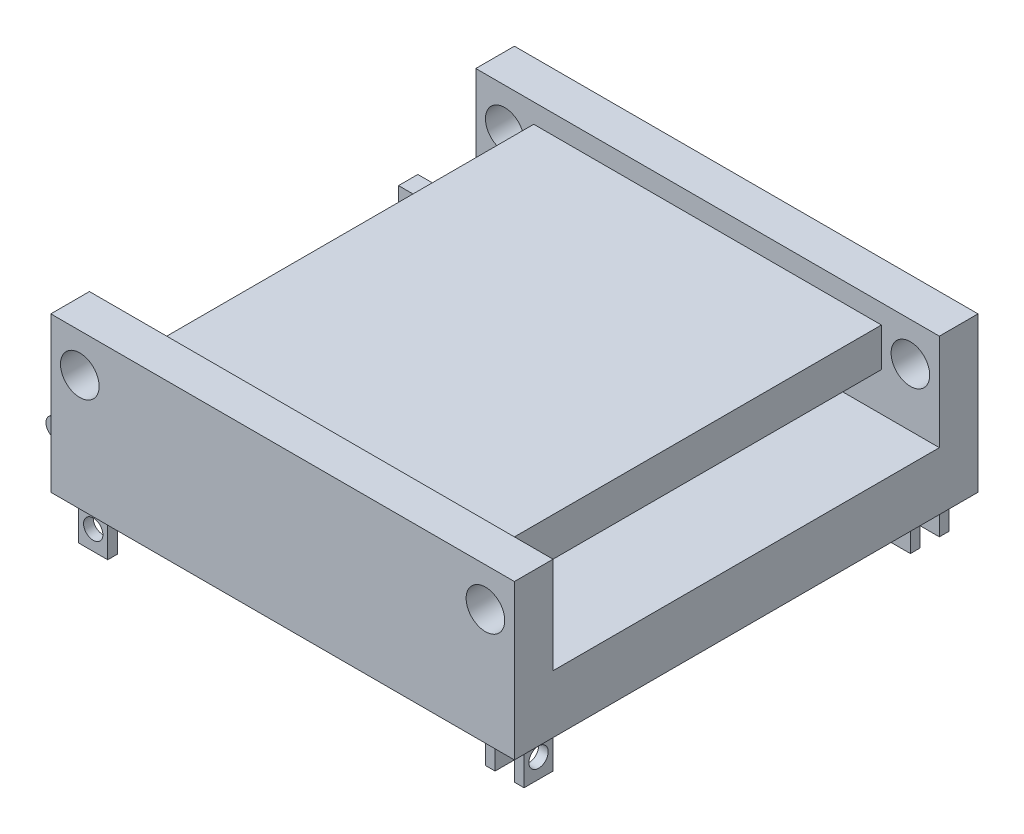
SolidWorks part; units mm, degrees
ref_plane "Front Plane" through (0, 0, 0) normal (0, 0, 1) x (1, 0, 0)
ref_plane "Top Plane" through (0, 0, 0) normal (0, 1, 0) x (1, 0, 0)
ref_plane "Right Plane" through (0, 0, 0) normal (1, 0, 0) x (0, 0, -1)
sketch "Sketch1" plane through (0, 0, 0) normal (0, 1, 0) x (1, 0, 0)
  line L0 (0, 0) -> (1219.2, 0)
  line L1 (1219.2, 0) -> (1219.2, 101.6)
  line L2 (1219.2, 101.6) -> (1117.6, 101.6)
  line L3 (1117.6, 101.6) -> (1117.6, 1117.6)
  line L4 (1117.6, 1117.6) -> (1219.2, 1117.6)
  line L5 (1219.2, 1117.6) -> (1219.2, 1219.2)
  line L6 (1219.2, 1219.2) -> (0, 1219.2)
  line L7 (0, 1219.2) -> (0, 1117.6)
  line L8 (0, 1117.6) -> (101.6, 1117.6)
  line L9 (101.6, 1117.6) -> (101.6, 101.6)
  line L10 (101.6, 101.6) -> (0, 101.6)
  line L11 (0, 101.6) -> (0, 0)
extrude "Boss-Extrude1" add sketch "Sketch1" along normal blind 203.2
sketch "Sketch2" plane through (0, 203.2, 0) normal (0, 1, 0) x (1, 0, 0)
  line L0 (101.6, 1117.6) -> (1117.6, 1117.6)
  line L1 (1117.6, 1117.6) -> (1117.6, 101.6)
  line L2 (1219.2, 101.6) -> (1117.6, 101.6) construction
  line L3 (1117.6, 101.6) -> (1117.6, 1117.6) construction
  line L4 (1117.6, 101.6) -> (101.6, 101.6)
  line L5 (101.6, 101.6) -> (101.6, 1117.6)
extrude "Cut-Extrude1" cut sketch "Sketch2" against normal blind 50.8
sketch "Sketch3" plane through (0, 0, 0) normal (0, -1, 0) x (-1, 0, 0)
  line L0 (-101.6, 101.6) -> (-1117.6, 101.6)
  line L1 (-1117.6, 101.6) -> (-1117.6, 1117.6)
  line L2 (-1117.6, 1117.6) -> (-101.6, 1117.6)
  line L3 (-101.6, 1117.6) -> (-101.6, 101.6)
extrude "Cut-Extrude2" cut sketch "Sketch3" against normal blind 50.8
sketch "Sketch4" plane through (1117.6, 0, 0) normal (1, 0, 0) x (0, 0, -1)
  line L0 (101.6, 152.4) -> (1117.6, 152.4)
  line L1 (1117.6, 152.4) -> (1117.6, 50.8)
  line L2 (1117.6, 50.8) -> (101.6, 50.8)
  line L3 (101.6, 50.8) -> (101.6, 152.4)
extrude "Cut-Extrude3" cut sketch "Sketch4" against normal blind 50.8
sketch "Sketch5" plane through (101.6, 0, 0) normal (-1, 0, 0) x (0, 0, 1)
  line L0 (-1117.6, 152.4) -> (-101.6, 152.4)
  line L1 (-101.6, 152.4) -> (-101.6, 50.8)
  line L2 (-101.6, 50.8) -> (-1117.6, 50.8)
  line L3 (-1117.6, 50.8) -> (-1117.6, 152.4)
extrude "Cut-Extrude4" cut sketch "Sketch5" against normal blind 50.8
sketch "Sketch6" plane through (0, 0, 0) normal (0, 0, 1) x (1, 0, 0)
  line L0 (1219.2, 101.6) -> (1143, 101.6)
  line L1 (1219.2, 203.2) -> (1219.2, 0) construction
  circle A0 centre (1143, 101.6) radius 50.8
extrude "Cut-Extrude5" cut sketch "Sketch6" against normal blind 1270
sketch "Sketch7" plane through (0, 0, -1219.2) normal (0, 0, -1) x (-1, 0, 0)
  line L0 (0, 101.6) -> (-76.2, 101.6)
  line L1 (0, 203.2) -> (0, 0) construction
  circle A0 centre (-76.2, 101.6) radius 50.8
extrude "Cut-Extrude6" cut sketch "Sketch7" against normal blind 1270
sketch "Sketch8" plane through (0, 0, 0) normal (0, -1, 0) x (-1, 0, 0)
  line L0 (0, 0) -> (-1219.2, 0)
  line L1 (-1219.2, 0) -> (-1219.2, 101.6)
  line L2 (-1219.2, 101.6) -> (0, 101.6)
  line L3 (0, 101.6) -> (0, 0)
  line L4 (0, 1117.6) -> (-1219.2, 1117.6)
  line L5 (-1219.2, 1117.6) -> (-1219.2, 1219.2)
  line L6 (-1219.2, 1219.2) -> (0, 1219.2)
  line L7 (0, 1219.2) -> (0, 1117.6)
extrude "Boss-Extrude2" add sketch "Sketch8" along normal blind 101.6
sketch "Sketch9" plane through (0, -101.6, 0) normal (0, -1, 0) x (-1, 0, 0)
  line L0 (-1219.2, 1219.2) -> (0, 1219.2)
  line L1 (0, 1219.2) -> (0, 0)
  line L2 (0, 0) -> (-1219.2, 0)
  line L3 (-1219.2, 0) -> (-1219.2, 1219.2)
extrude "Boss-Extrude4" add sketch "Sketch9" along normal blind 101.6
sketch "Sketch10" plane through (0, -203.2, 0) normal (0, -1, 0) x (-1, 0, 0)
  line L0 (0, 0) -> (0, 127)
  line L1 (0, 0) -> (0, 1219.2) construction
  line L2 (0, 127) -> (-127, 127)
  line L3 (-1219.2, 0) -> (-1219.2, 127)
  line L4 (-1219.2, 1219.2) -> (-1219.2, 0) construction
  line L5 (-127, 1092.2) -> (-101.6, 1092.2)
  line L6 (-1219.2, 1219.2) -> (-1219.2, 1092.2)
  line L7 (-1219.2, 1092.2) -> (-1092.2, 1092.2)
  line L8 (0, 1219.2) -> (0, 1092.2)
  line L9 (-127, 1092.2) -> (-127, 1219.2)
  line L10 (0, 1219.2) -> (-1219.2, 1219.2) construction
  line L11 (-101.6, 1092.2) -> (-101.6, 1168.4)
  line L12 (-101.6, 1168.4) -> (-127, 1168.4)
  line L13 (-101.6, 1168.4) -> (-50.8, 1168.4)
  line L17 (-127, 1193.8) -> (-127, 1168.4)
  line L18 (-1092.2, 1092.2) -> (-1092.2, 1117.6)
  line L19 (-1092.2, 1117.6) -> (-1168.4, 1117.6)
  line L20 (-1168.4, 1117.6) -> (-1168.4, 1092.2)
  line L21 (-1168.4, 1117.6) -> (-1168.4, 1168.4)
  line L22 (-1168.4, 1168.4) -> (-1168.4, 1193.8)
  line L23 (-1168.4, 1193.8) -> (-1092.2, 1193.8)
  line L24 (-1092.2, 1193.8) -> (-1092.2, 1168.4)
  line L25 (-1092.2, 1168.4) -> (-1168.4, 1168.4)
  line L26 (-127, 127) -> (-127, 101.6)
  line L27 (-127, 101.6) -> (-50.8, 101.6)
  line L28 (-50.8, 101.6) -> (-50.8, 127)
  line L29 (-50.8, 127) -> (-50.8, 48.0375)
  line L30 (-50.8, 48.0375) -> (-50.8, 22.6375)
  line L31 (-50.8, 22.6375) -> (-127, 22.6375)
  line L32 (-127, 22.6375) -> (-127, 48.0375)
  line L33 (-127, 48.0375) -> (-50.8, 48.0375)
  line L34 (-1092.2, 127) -> (-1092.2, 0)
  line L35 (-1219.2, 0) -> (0, 0) construction
  line L36 (-50.8, 1168.4) -> (-25.4, 1168.4)
  line L37 (-25.4, 1168.4) -> (-25.4, 1092.2)
  line L38 (-25.4, 1092.2) -> (-50.8, 1092.2)
  line L39 (-50.8, 1092.2) -> (-50.8, 1168.4)
  line L40 (-1092.2, 127) -> (-1117.6, 127)
  line L41 (-1117.6, 127) -> (-1117.6, 50.8)
  line L42 (-1117.6, 50.8) -> (-1092.2, 50.8)
  line L43 (-1092.2, 50.8) -> (-1168.4, 50.8)
  line L44 (-1168.4, 50.8) -> (-1168.4, 127)
  line L45 (-1168.4, 127) -> (-1193.8, 127)
  line L46 (-1193.8, 127) -> (-1193.8, 50.8)
  line L47 (-1193.8, 50.8) -> (-1168.4, 50.8)
extrude "Boss-Extrude5" add sketch "Sketch10" along normal blind 101.6 contours L41 L42 L34 L40 | L46 L47 L44 L45 | L27 L28 L2 L26 | L33 L32 L31 L30 | L19 L20 L7 L18 | L25 L24 L23 L22 | L39 L38 L37 L36 | L11 L12 L9 L5
sketch "Sketch12" plane through (1193.8, 0, 0) normal (1, 0, 0) x (0, 0, -1)
  line L0 (88.9, -203.2) -> (88.9, -254)
  line L1 (127, -203.2) -> (50.8, -203.2) construction
  circle A0 centre (88.9, -254) radius 25.4
extrude "Cut-Extrude7" cut sketch "Sketch12" against normal blind 203.2
sketch "Sketch13" plane through (0, 0, -1193.8) normal (0, 0, -1) x (-1, 0, 0)
  line L0 (-1130.3, -203.2) -> (-1130.3, -254)
  line L1 (-1168.4, -203.2) -> (-1092.2, -203.2) construction
  circle A0 centre (-1130.3, -254) radius 25.4
extrude "Cut-Extrude8" cut sketch "Sketch13" against normal blind 203.2
sketch "Sketch14" plane through (25.4, 0, 0) normal (-1, 0, 0) x (0, 0, 1)
  line L0 (-1130.3, -203.2) -> (-1130.3, -254)
  line L1 (-1168.4, -203.2) -> (-1092.2, -203.2) construction
  circle A0 centre (-1130.3, -254) radius 25.4
extrude "Cut-Extrude9" cut sketch "Sketch14" against normal blind 203.2
sketch "Sketch15" plane through (0, 0, -22.6375) normal (0, 0, 1) x (1, 0, 0)
  line L0 (88.9, -203.2) -> (88.9, -254)
  line L1 (50.8, -203.2) -> (127, -203.2) construction
  circle A0 centre (88.9, -254) radius 25.4
extrude "Cut-Extrude10" cut sketch "Sketch15" against normal blind 203.2
sketch "Sketch16" plane through (0, 0, 0) normal (-1, 0, 0) x (0, 0, 1)
  line L0 (-1117.6, -101.6) -> (-1117.6, -50.8)
  line L1 (-1117.6, 203.2) -> (-1117.6, -101.6) construction
  line L2 (-1117.6, -50.8) -> (-101.6, -50.8)
  line L3 (-101.6, 203.2) -> (-101.6, -101.6) construction
  line L4 (-101.6, -50.8) -> (-101.6, -101.6)
  line L5 (-101.6, -101.6) -> (-1117.6, -101.6) construction
  line L6 (-101.6, -101.6) -> (-1117.6, -101.6)
extrude "Boss-Extrude6" add sketch "Sketch16" against normal blind 1219.2
sketch "Sketch17" plane through (0, 0, 0) normal (-1, 0, 0) x (0, 0, 1)
  line L0 (-609.6, -50.8) -> (-609.6, -127)
  line L1 (-101.6, -50.8) -> (-1117.6, -50.8) construction
  line L2 (-609.6, -127) -> (-177.8, -127)
  line L3 (-609.6, -127) -> (-1041.4, -127)
  line L4 (-177.8, -127) -> (-177.8, -88.9)
  line L5 (-177.8, -88.9) -> (-127, -88.9)
  line L6 (-127, -88.9) -> (-127, -165.1)
  line L7 (-127, -165.1) -> (-177.8, -165.1)
  line L8 (-177.8, -165.1) -> (-177.8, -127)
  line L9 (-1041.4, -127) -> (-1041.4, -88.9)
  line L10 (-1041.4, -88.9) -> (-1092.2, -88.9)
  line L11 (-1092.2, -88.9) -> (-1092.2, -165.1)
  line L12 (-1092.2, -165.1) -> (-1041.4, -165.1)
  line L13 (-1041.4, -165.1) -> (-1041.4, -127)
extrude "Boss-Extrude7" add sketch "Sketch17" along normal blind 127 contours L12 L13 L9 L10 L11 | L4 L5 L6 L7 L8
sketch "Sketch18" plane through (0, 0, -1092.2) normal (0, 0, -1) x (-1, 0, 0)
  line L0 (0, -127) -> (63.5, -127)
  line L1 (0, -88.9) -> (0, -165.1) construction
  circle A0 centre (63.5, -127) radius 25.4
extrude "Boss-Extrude8" add sketch "Sketch18" along normal blind 50.8
sketch "Sketch19" plane through (0, 0, -127) normal (0, 0, 1) x (1, 0, 0)
  line L0 (0, -127) -> (-63.5, -127)
  line L1 (0, -88.9) -> (0, -165.1) construction
  circle A0 centre (-63.5, -127) radius 25.4
extrude "Boss-Extrude9" add sketch "Sketch19" along normal blind 50.8
